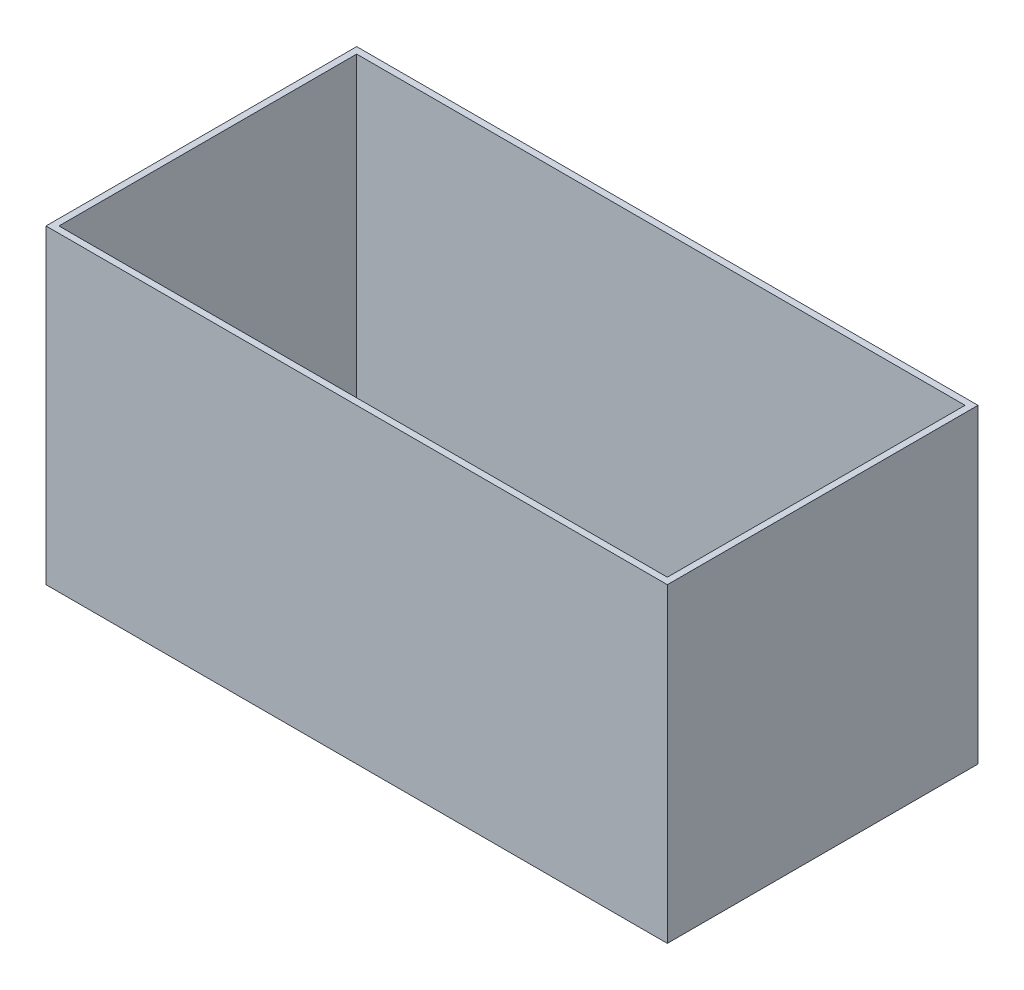
SolidWorks part; units mm, degrees
ref_plane "Front Plane" through (0, 0, 0) normal (0, 0, 1) x (1, 0, 0)
ref_plane "Top Plane" through (0, 0, 0) normal (0, 1, 0) x (1, 0, 0)
ref_plane "Right Plane" through (0, 0, 0) normal (1, 0, 0) x (0, 0, -1)
sketch "Sketch1" plane through (0, 0, 0) normal (0, 1, 0) x (1, 0, 0)
  line L1 (0, 0) -> (609.6, 0)
  line L2 (0, 0) -> (0, 304.8)
  line L3 (0, 304.8) -> (609.6, 304.8)
  line L4 (609.6, 0) -> (609.6, 304.8)
  dimension "D1" = 609.6
  dimension "D2" = 304.8
extrude "Boss-Extrude1" add sketch "Sketch1" along normal blind 304.8
sketch "Sketch2" plane through (0, 304.8, 0) normal (0, 1, 0) x (1, 0, 0)
  line L0 (609.6, 0) -> (609.6, 304.8) construction
  line L1 (6.35, 6.35) -> (603.25, 6.35)
  line L2 (6.35, 6.35) -> (6.35, 298.45)
  line L3 (6.35, 298.45) -> (603.25, 298.45)
  line L4 (603.25, 6.35) -> (603.25, 298.45)
  line L5 (6.35, 6.35) -> (603.25, 298.45) construction
  line L6 (6.35, 298.45) -> (603.25, 6.35) construction
  line L7 (609.6, 304.8) -> (0, 304.8) construction
  point P0 (304.8, 152.4)
  dimension "D1" = 304.8
  dimension "D2" = 152.4
  dimension "D3" = 6.35
  dimension "D4" = 6.35
extrude "Cut-Extrude1" cut sketch "Sketch2" against normal blind 298.45 contours L3 L4 L1 L2
